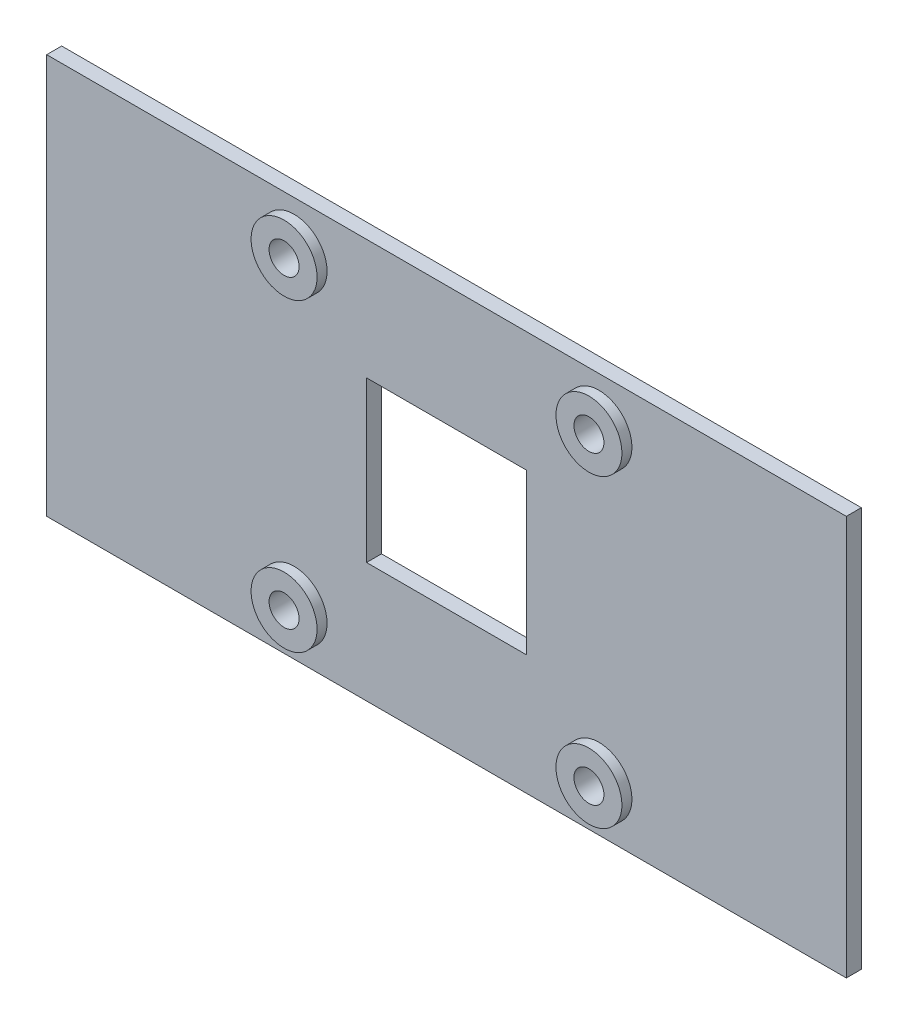
SolidWorks part; units mm, degrees
ref_plane "前视基准面" through (0, 0, 0) normal (0, 0, 1) x (1, 0, 0)
ref_plane "上视基准面" through (0, 0, 0) normal (0, 1, 0) x (1, 0, 0)
ref_plane "右视基准面" through (0, 0, 0) normal (1, 0, 0) x (0, 0, -1)
other "图形1"
sketch "草图2" plane through (0, 0, 0) normal (0, 0, 1) x (1, 0, 0)
  line L0 (-47.2291, 0.2568) -> (32.7709, 0.2568) construction
  line L1 (-47.2291, 20.2568) -> (32.7709, 20.2568)
  line L2 (-47.2291, 20.2568) -> (-47.2291, -19.7432)
  line L3 (-47.2291, -19.7432) -> (32.7709, -19.7432)
  line L4 (32.7709, 20.2568) -> (32.7709, -19.7432)
  line L5 (-7.2291, 20.2568) -> (-7.2291, -19.7432) construction
  line L6 (-7.2291, -7.7432) -> (0.7709, -7.7432)
  line L7 (0.7709, -7.7432) -> (0.7709, 8.2568)
  line L8 (0.7709, 8.2568) -> (-15.2291, 8.2568)
  line L9 (-15.2291, 8.2568) -> (-15.2291, -7.7432)
  line L10 (-15.2291, -7.7432) -> (-7.2291, -7.7432)
  circle A0 centre (-22.4791, 15.5068) radius 1.5
  circle A1 centre (8.0209, 15.5068) radius 1.5
  circle A2 centre (8.0209, -14.9932) radius 1.5
  circle A3 centre (-22.4791, -14.9932) radius 1.5
  dimension "D1" = 15.25
  dimension "D3" = 8
  dimension "D5" = 40
  dimension "D7" = 16
  dimension "D2" = 15.25
  dimension "D4" = 8
  dimension "D6" = 80
  dimension "D8" = 8
extrude "凸台-拉伸1" add sketch "草图2" along normal blind 1.5
sketch "草图3" plane through (0, 0, 1.5) normal (0, 0, 1) x (1, 0, 0)
  circle A0 centre (-22.4791, 15.5068) radius 1.5
  circle A1 centre (8.0209, 15.5068) radius 1.5
  circle A2 centre (8.0209, -14.9932) radius 1.5
  circle A3 centre (-22.4791, -14.9932) radius 1.5
  circle A4 centre (-22.4791, 15.5068) radius 3.3
  circle A5 centre (8.0209, 15.5068) radius 3.3
  circle A6 centre (-22.4791, -14.9932) radius 3.3
  circle A7 centre (8.0209, -14.9932) radius 3.3
extrude "凸台-拉伸2" add sketch "草图3" along normal blind 1
